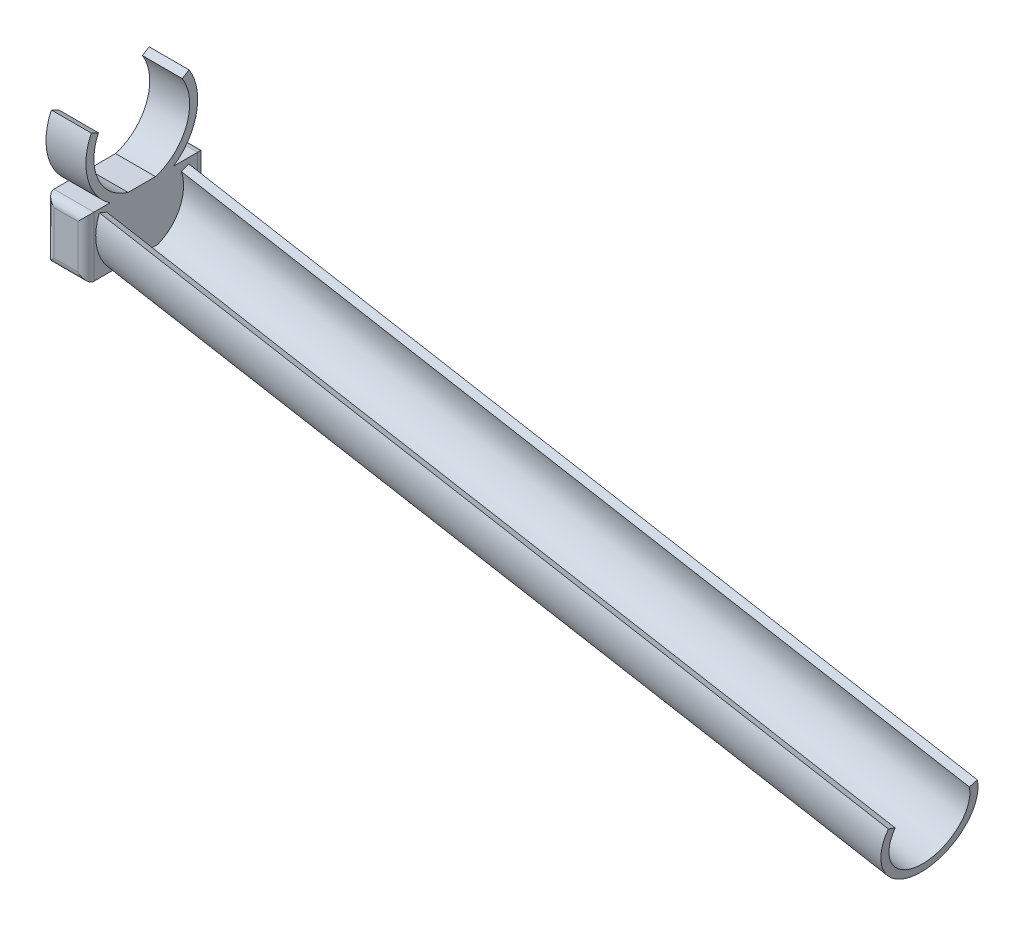
SolidWorks part; units mm, degrees
ref_plane "前视基准面" through (0, 0, 0) normal (0, 0, 1) x (1, 0, 0)
ref_plane "上视基准面" through (0, 0, 0) normal (0, 1, 0) x (1, 0, 0)
ref_plane "右视基准面" through (0, 0, 0) normal (1, 0, 0) x (0, 0, -1)
other "Configuration Table"
sketch "草图1" plane through (0, 0, 0) normal (1, 0, 0) x (0, 0, -1)
  circle A0 centre (0, 0) radius 12 construction
  arc A1 (-10.8461, 5.1343) -> (10.1539, 6.3952) centre (0, 0) ccw
  dimension "D1" = 24
  dimension "D2" = 24
  dimension "D3" = 21
extrude "拉伸-薄壁1" add sketch "草图1" along normal blind 10 thin
ref_plane "基准面1" through (0, -14, 0) normal (0, -1, 0) x (-1, 0, 0)
sketch "草图2" plane through (0, -14, 0) normal (0, -1, 0) x (-1, 0, 0)
  line L0 (-10, 14) -> (-10, -14) construction
  line L1 (-10, 16) -> (0, 16)
  line L2 (-10, 16) -> (-10, -14)
  line L3 (-10, -14) -> (0, -14)
  line L4 (0, 16) -> (0, -14)
extrude "凸台-拉伸1" add sketch "草图2" along normal mid plane 5
ref_plane "基准面3" through (12.5201, -2.2076, 0) normal (0.9848, -0.1736, 0) x (0, 0, 1)
sketch "草图6" plane through (12.5201, -2.2076, 0) normal (0.9848, -0.1736, 0) x (0, 0, 1)
  arc A0 (-11.7827, 11.0145) -> (10.6229, 10.4083) centre (-0.4639, 15) cw
  dimension "D3" = 24
  dimension "D1" = 15
extrude "拉伸-薄壁4" add sketch "草图6" along normal blind 200 and the other way blind 1 separate body thin
sketch "草图8" plane through (0, -16.5, 0) normal (0, -1, 0) x (1, 0, 0)
  line L4 (10, -16) -> (10, 14)
  line L5 (10, 14) -> (0, 14)
  line L6 (0, 14) -> (0, -16)
  line L7 (0, -16) -> (10, -16)
  line L8 (10, -16) -> (10, 14)
  line L9 (10, 14) -> (0, 14)
  line L10 (0, 14) -> (0, -16)
  line L11 (0, -16) -> (10, -16)
  dimension "D1" = 0
extrude "凸台-拉伸2" add sketch "草图8" along normal blind 10
fillet "圆角2" radius 2 8 edges at (10, -19, 14) (5, -26.5, 14) (0, -19, 14) (5, -11.5, 14) (0, -19, -16) (5, -26.5, -16) (10, -19, -16) (5, -11.5, -16)
sketch "草图9" plane through (0, 0, 0) normal (0, 1, 0) x (1, 0, 0)
  line L0 (23.8674, 0) -> (221.8036, 0)
  line L1 (234.7114, 12.9078) -> (234.7114, 61.3087)
  arc A0 (221.8036, 0) -> (234.7114, 12.9078) centre (221.8036, 12.9078) ccw
sketch "草图10" plane through (0, 0, 0) normal (1, 0, 0) x (0, 0, -1)
  line L0 (6.036, -3) -> (8.036, -3)
  line L1 (-6.036, -3) -> (-8.036, -3)
  arc A0 (-6.036, -3) -> (6.036, -3) centre (0, -3) ccw
  arc A1 (-8.036, -3) -> (8.036, -3) centre (0, -3) ccw
  dimension "D1" = 6.036
  dimension "D2" = 3
  dimension "D3" = 2
  dimension "D4" = 2
